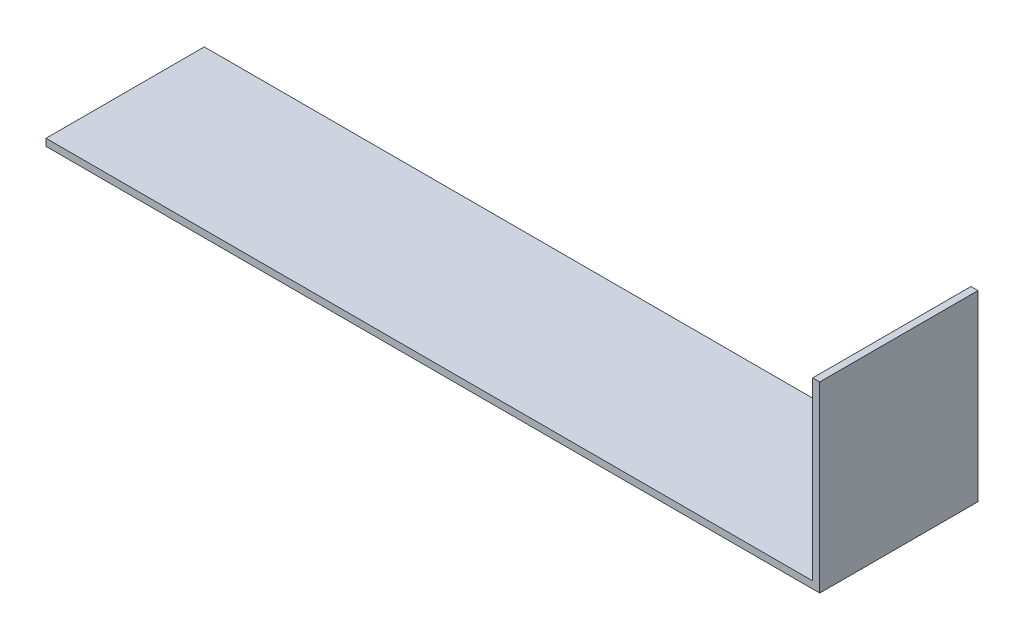
SolidWorks part; units mm, degrees
ref_plane "前视基准面" through (0, 0, 0) normal (0, 0, 1) x (1, 0, 0)
ref_plane "上视基准面" through (0, 0, 0) normal (0, 1, 0) x (1, 0, 0)
ref_plane "右视基准面" through (0, 0, 0) normal (1, 0, 0) x (0, 0, -1)
sketch "草图1" plane through (0, 0, 0) normal (0, 1, 0) x (1, 0, 0)
  line L1 (110, -22.5) -> (-110, -22.5)
  line L2 (110, -22.5) -> (110, 22.5)
  line L3 (110, 22.5) -> (-110, 22.5)
  line L4 (-110, -22.5) -> (-110, 22.5)
  line L5 (110, -22.5) -> (-110, 22.5) construction
  line L6 (110, 22.5) -> (-110, -22.5) construction
  point P0 (0, 0)
  dimension "D1" = 220
  dimension "D2" = 45
extrude "凸台-拉伸1" add sketch "草图1" along normal blind 2
sketch "草图2" plane through (0, 2, 0) normal (0, 1, 0) x (1, 0, 0)
  line L0 (-110, -22.5) -> (110, -22.5) construction
  line L1 (110, 22.5) -> (108, 22.5)
  line L2 (110, 22.5) -> (110, -22.5)
  line L3 (110, -22.5) -> (108, -22.5)
  line L4 (108, 22.5) -> (108, -22.5)
  dimension "D1" = 2
extrude "凸台-拉伸2" add sketch "草图2" along normal blind 50
